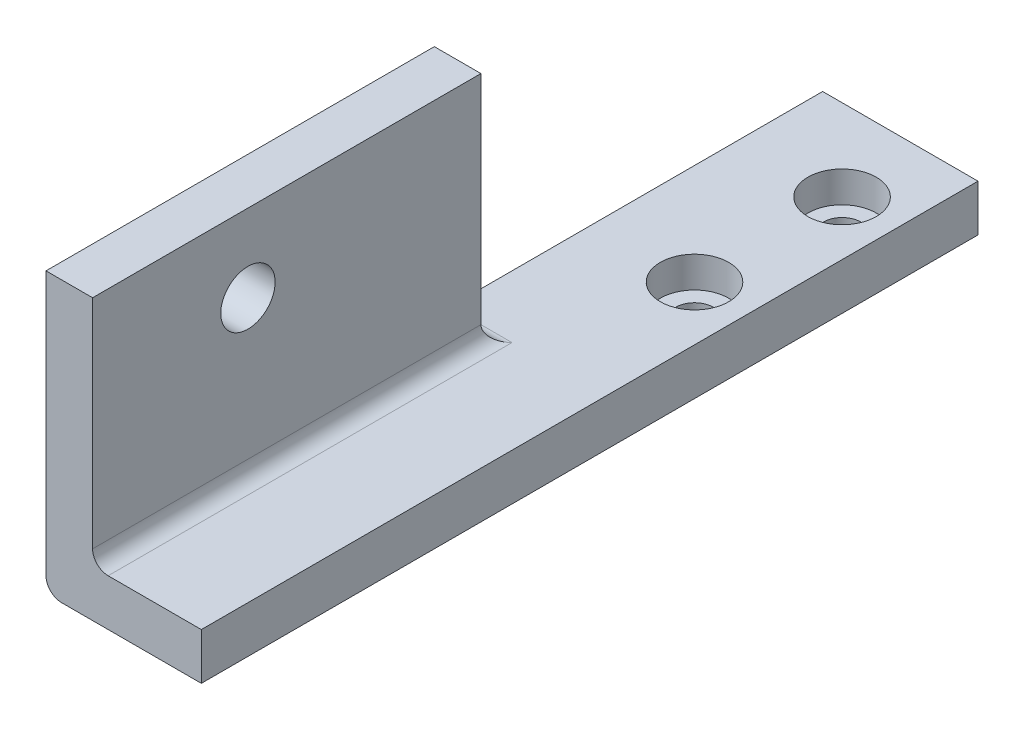
SolidWorks part; units mm, degrees
ref_plane "Front Plane" through (0, 0, 0) normal (0, 0, 1) x (1, 0, 0)
ref_plane "Top Plane" through (0, 0, 0) normal (0, 1, 0) x (1, 0, 0)
ref_plane "Right Plane" through (0, 0, 0) normal (1, 0, 0) x (0, 0, -1)
sketch "Sketch1" plane through (0, 0, 0) normal (0, 1, 0) x (1, 0, 0)
  line L0 (6.5, 5.25) -> (6.5, 14.75) construction
  line L1 (0, 0) -> (10, 0)
  line L2 (0, 0) -> (0, 20)
  line L3 (0, 20) -> (10, 20)
  line L4 (10, 0) -> (10, 20)
  circle A0 centre (6.5, 5.25) radius 1.175
  circle A1 centre (6.5, 14.75) radius 1.175
  point P9 (6.5, 10)
  point P10 (10, 10)
  dimension "D3" = 9.5
  dimension "D4" = 2.35
  dimension "D5" = 2.35
  dimension "D6" = 6.5
  dimension "D1" = 20
  dimension "D2" = 10
extrude "Boss-Extrude1" add sketch "Sketch1" along normal blind 3
sketch "Sketch2" plane through (0, 3, 0) normal (0, 1, 0) x (1, 0, 0)
  point P0 (6.5, 14.75)
  point P1 (6.5, 5.25)
hole_wizard "CBORE for M2 SHCS1" positions "Sketch2" profile "Sketch3" counterbore size "M2" standard "ANSI Metric" end condition through all
sketch "Sketch3" plane through (6.5, 3, -14.75) normal (1, 0, 0) x (0, 0, 1)
  line L0 (0, 0) -> (0, 3)
  line L1 (0, 3) -> (1.2, 3)
  line L3 (1.2, 3) -> (1.2, 2)
  line L4 (1.2, 2) -> (2.2, 2)
  line L5 (2.2, 2) -> (2.2, 0)
  line L7 (2.2, 0) -> (0, 0)
  line L11 (0, -6.35) -> (0, 107.95) construction
  dimension "Thru Hole Dia." = 2.4
  dimension "Thru Hole Depth" = 3
  dimension "C'Bore Dia." = 4.4
  dimension "C'Bore Depth" = 2
sketch "Sketch6" plane through (0, 0, 0) normal (0, 0, -1) x (-1, 0, 0)
  line L1 (0, 0) -> (-10, 0)
  line L2 (0, 0) -> (0, 3)
  line L3 (0, 3) -> (-10, 3)
  line L4 (-10, 0) -> (-10, 3)
  line L5 (-10, 3) -> (0, 3) construction
  line L6 (-10, 3) -> (-10, 0) construction
  dimension "D1" = 0
extrude "Boss-Extrude2" add sketch "Sketch6" against normal blind 30
sketch "Sketch8" plane through (0, 3, 0) normal (0, 1, 0) x (1, 0, 0)
  line L2 (0, -30) -> (3, -30)
  line L3 (0, -30) -> (0, -5)
  line L4 (0, -5) -> (3, -5)
  line L5 (3, -30) -> (3, -5)
  dimension "D1" = 3
  dimension "D2" = 25
extrude "Boss-Extrude3" add sketch "Sketch8" along normal blind 15
sketch "Sketch9" plane through (3, 0, 0) normal (1, 0, 0) x (0, 0, -1)
  line L1 (20, 3) -> (-30, 3) construction
  line L2 (-30, 18) -> (-30, 3) construction
  circle A0 centre (-20, 13) radius 1.75
  dimension "D1" = 10
  dimension "D2" = 10
  dimension "D3" = 3.5
extrude "Cut-Extrude1" cut sketch "Sketch9" against normal through all
fillet "Fillet1" radius 1 2 edges at (1.5, 3, 5) (3, 3, 17.5)
fillet "Fillet2" radius 1 1 edges at (0, 0, 5)
